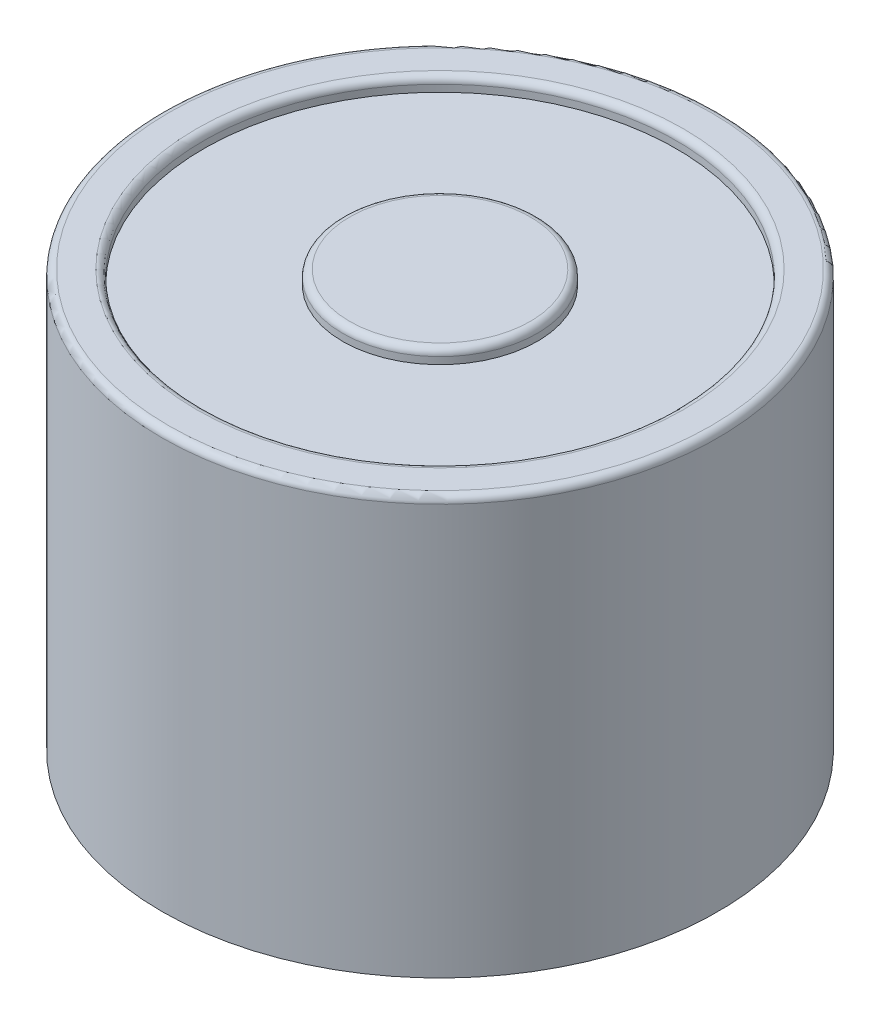
SolidWorks part; units mm, degrees
ref_plane "Front Plane" through (0, 0, 0) normal (0, 0, 1) x (1, 0, 0)
ref_plane "Top Plane" through (0, 0, 0) normal (0, 1, 0) x (1, 0, 0)
ref_plane "Right Plane" through (0, 0, 0) normal (1, 0, 0) x (0, 0, -1)
sketch "Sketch1" plane through (0, 0, 0) normal (0, 1, 0) x (1, 0, 0)
  circle A0 centre (0, 0) radius 10
  dimension "D1" = 20
extrude "Boss-Extrude1" add sketch "Sketch1" along normal blind 15
sketch "Sketch2" plane through (0, 15, 0) normal (0, 1, 0) x (1, 0, 0)
  circle A2 centre (0, 0) radius 8.5
  circle A3 centre (0, 0) radius 8.5
  dimension "D1" = 1.5
extrude "Cut-Extrude1" cut sketch "Sketch2" against normal blind 0.5
sketch "Sketch3" plane through (0, 14.5, 0) normal (0, 1, 0) x (1, 0, 0)
  circle A0 centre (0, 0) radius 3.5
  dimension "D1" = 7
extrude "Boss-Extrude2" add sketch "Sketch3" along normal blind 0.5
fillet "Fillet1" radius 0.25 3 edges at (0, 15, 3.5) (0, 15, 8.5) (0, 15, 10)
